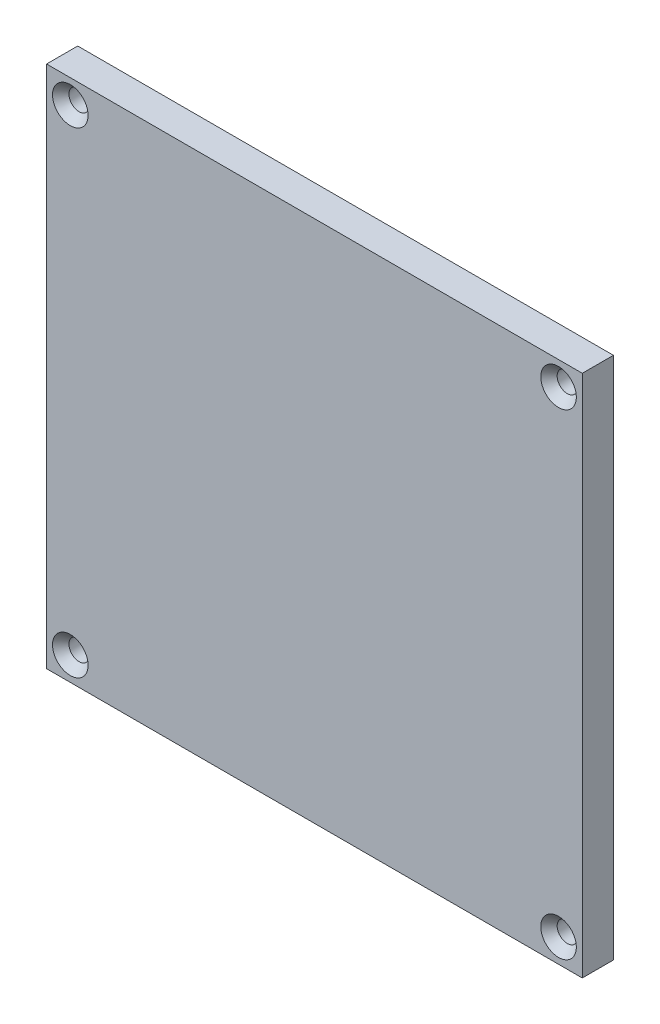
SolidWorks part; units mm, degrees
ref_plane "Front" through (0, 0, 0) normal (0, 0, 1) x (1, 0, 0)
ref_plane "Top" through (0, 0, 0) normal (0, 1, 0) x (1, 0, 0)
ref_plane "Right" through (0, 0, 0) normal (1, 0, 0) x (0, 0, -1)
sketch "Sketch1" plane through (0, 0, 0) normal (0, 0, 1) x (1, 0, 0)
  line L1 (-43, -42.037) -> (43, -42.037)
  line L2 (-43, -42.037) -> (-43, 42.037)
  line L3 (-43, 42.037) -> (43, 42.037)
  line L4 (43, -42.037) -> (43, 42.037)
  line L5 (-43, -42.037) -> (43, 42.037) construction
  line L6 (-43, 42.037) -> (43, -42.037) construction
  point P0 (0, 0)
  dimension "D1" = 86
  dimension "D2" = 84.074
extrude "Boss-Extrude1" add sketch "Sketch1" along normal blind 5
hole_wizard "CSK for #4 Flat Head Machine Screw1" positions "Sketch2" profile "Sketch3" countersink size "#4" standard "ANSI Inch" end condition up to next
sketch "Sketch2" plane through (0, 0, 5) normal (0, 0, 1) x (1, 0, 0)
  line L0 (43, 42.037) -> (-43, 42.037) construction
  line L1 (-43, 42.037) -> (-43, -42.037) construction
  line L2 (43, -42.037) -> (43, 42.037) construction
  line L3 (-43, -42.037) -> (43, -42.037) construction
  point P0 (-39.19, 38.227)
  point P2 (39.19, 38.227)
  point P4 (-39.19, -38.227)
  point P6 (39.19, -38.227)
  dimension "D1" = 3.81
  dimension "D2" = 3.81
  dimension "D3" = 3.81
  dimension "D4" = 3.81
sketch "Sketch3" plane through (-39.19, 38.227, 5) normal (1, 0, 0) x (0, -1, 0)
  line L0 (0, 0) -> (0, 5)
  line L1 (0, 5) -> (1.6319, 5)
  line L2 (1.6319, 5) -> (1.6319, 1.4098)
  line L3 (1.6319, 1.4098) -> (2.8575, 0)
  line L5 (2.8575, 0) -> (0, 0)
  line L6 (-1.6319, 1.4098) -> (-2.8575, 0) construction
  line L11 (0, -6.35) -> (0, 107.95) construction
  dimension "Thru Hole Dia." = 3.2639
  dimension "Thru Hole Depth" = 5
  dimension "Near C'Sink Dia." = 5.715
  dimension "Near C'Sink Angle" = 82
equation "\"PCB Width\"= 1940mil"
equation "\"PCB Height\"= 2210mil"
equation "\"PCB Thickness\"= 63mil"
equation "\"Motor Bearing Diameter\"= 12mm"
equation "\"Motor Bearing Length\"= 5mm"
equation "\"Motor Body Front Diameter\"= 37mm"
equation "\"Motor Body Front Length\"= 30mm"
equation "\"Motor Body Back Length\"= 33.3mm"
equation "\"Motor PCD\"= 31mm"
equation "\"Large PVC Fittings Wall Thickness\"= 15in / 64"
equation "\"Large PVC Pipe Outer Diameter\"= 3.5in"
equation "\"Box Width\"= 2 * \"Motor Bearing Length\" + \"Motor Body Front Length\" + \"Motor Body Back Length\" + 0.5in"
equation "\"Box Hole Center to Edge Distance\"= 150mil"
equation "\"Box Ceiling and Floor Thickness\"= 2 * \"Box Hole Center to Edge Distance\""
equation "\"Box Height\"= 2 * \"Box Ceiling and Floor Thickness\" + \"PCB Height\" + 0.5in"
equation "\"Box Back Depth\"= \"Large PVC Fittings Wall Thickness\" + \"Large PVC Pipe Outer Diameter\" / 2 + \"Motor Body Front Diameter\" / 2"
equation "\"D1@Sketch1\"=\"Box Width\""
equation "\"D2@Sketch1\"=\"Box Height\""
equation "\"D1@Boss-Extrude1\"=\"Motor Bearing Length\""
equation "\"D1@Sketch2\"=\"Box Hole Center to Edge Distance\""
equation "\"D2@Sketch2\"=\"Box Hole Center to Edge Distance\""
equation "\"D3@Sketch2\"=\"Box Hole Center to Edge Distance\""
equation "\"D4@Sketch2\"=\"Box Hole Center to Edge Distance\""
